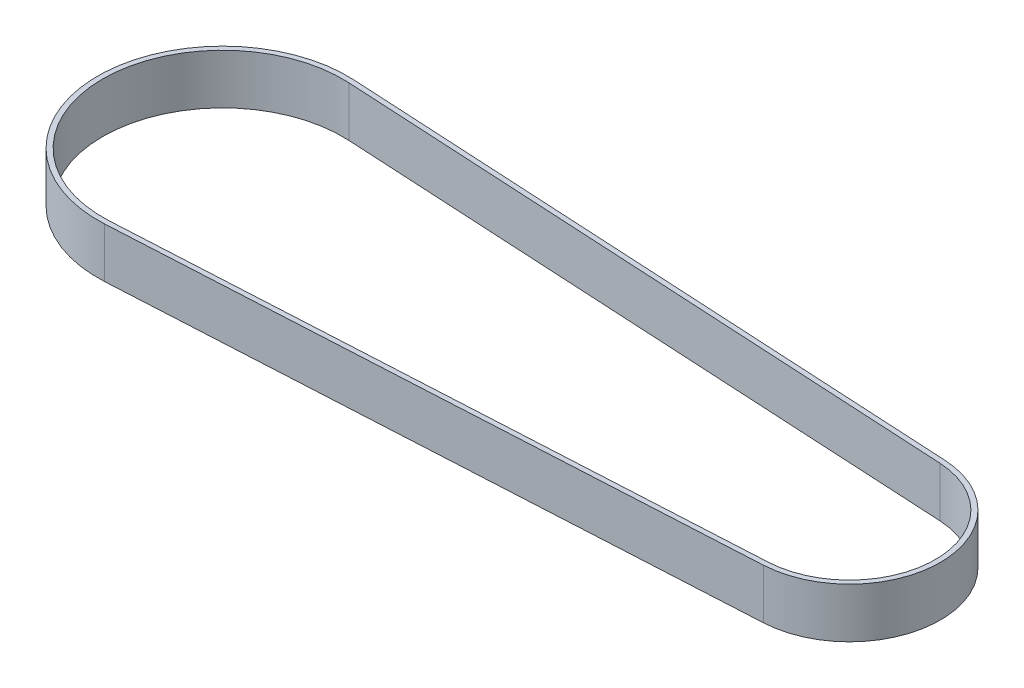
SolidWorks part; units mm, degrees
material "BUTYL"
ref_plane "Front Plane" through (0, 0, 0) normal (0, 0, 1) x (1, 0, 0)
ref_plane "Top Plane" through (0, 0, 0) normal (0, 1, 0) x (1, 0, 0)
ref_plane "Right Plane" through (0, 0, 0) normal (1, 0, 0) x (0, 0, -1)
sketch "Sketch1" plane through (0, 0, 0) normal (0, 1, 0) x (1, 0, 0)
  line L0 (0, 0) -> (125.5, 0) construction
  line L1 (1.3004, 23.9647) -> (126.432, 17.1747)
  line L2 (1.3546, 24.9633) -> (126.4861, 18.1733)
  line L3 (1.3546, -24.9633) -> (126.4861, -18.1733)
  line L4 (1.3004, -23.9647) -> (126.432, -17.1747)
  arc A0 (1.3004, 23.9647) -> (1.3004, -23.9647) centre (0, 0) ccw
  arc A1 (126.432, -17.1747) -> (126.432, 17.1747) centre (125.5, 0) ccw
  arc A2 (126.4861, -18.1733) -> (126.4861, 18.1733) centre (125.5, 0) ccw
  arc A3 (1.3546, 24.9633) -> (1.3546, -24.9633) centre (0, 0) ccw
  dimension "D1" = 48
  dimension "D3" = 34.4
  dimension "D2" = 125.5
  dimension "D4" = 1
extrude "Boss-Extrude1" add sketch "Sketch1" along normal blind 10
